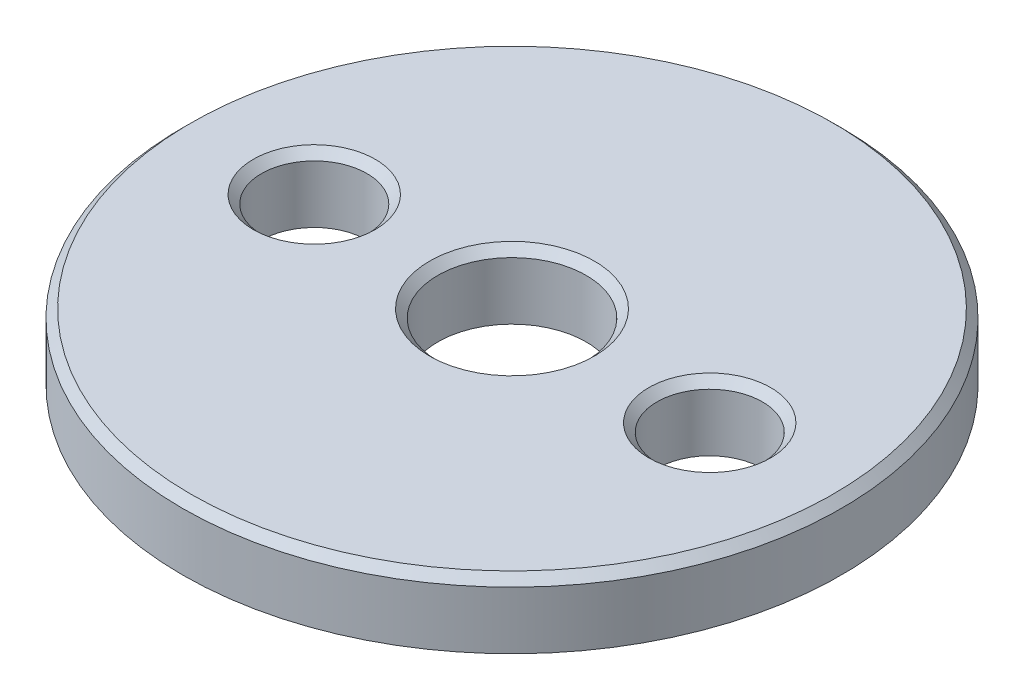
SolidWorks part; units mm, degrees
material "Alloy Steel"
ref_plane "Front Plane" through (0, 0, 0) normal (0, 0, 1) x (1, 0, 0)
ref_plane "Top Plane" through (0, 0, 0) normal (0, 1, 0) x (1, 0, 0)
ref_plane "Right Plane" through (0, 0, 0) normal (1, 0, 0) x (0, 0, -1)
sketch "Sketch1" plane through (0, 0, 0) normal (0, 1, 0) x (1, 0, 0)
  line L0 (-10, 0) -> (10, 0) construction
  circle A0 centre (0, 0) radius 10
  circle A1 centre (0, 0) radius 6 construction
  circle A2 centre (-6, 0) radius 1.6
  circle A3 centre (6, 0) radius 1.6
  circle A4 centre (0, 0) radius 2.25
  dimension "D1" = 20
  dimension "D2" = 3.2
  dimension "D3" = 3.2
  dimension "D4" = 4.5
  dimension "D5" = 12
extrude "Boss-Extrude1" add sketch "Sketch1" along normal blind 2
chamfer "Chamfer1" distance 0.25 angle 45 4 edges at (6, 2, 1.6) (0, 2, 2.25) (-6, 2, 1.6) (0, 2, 10)
